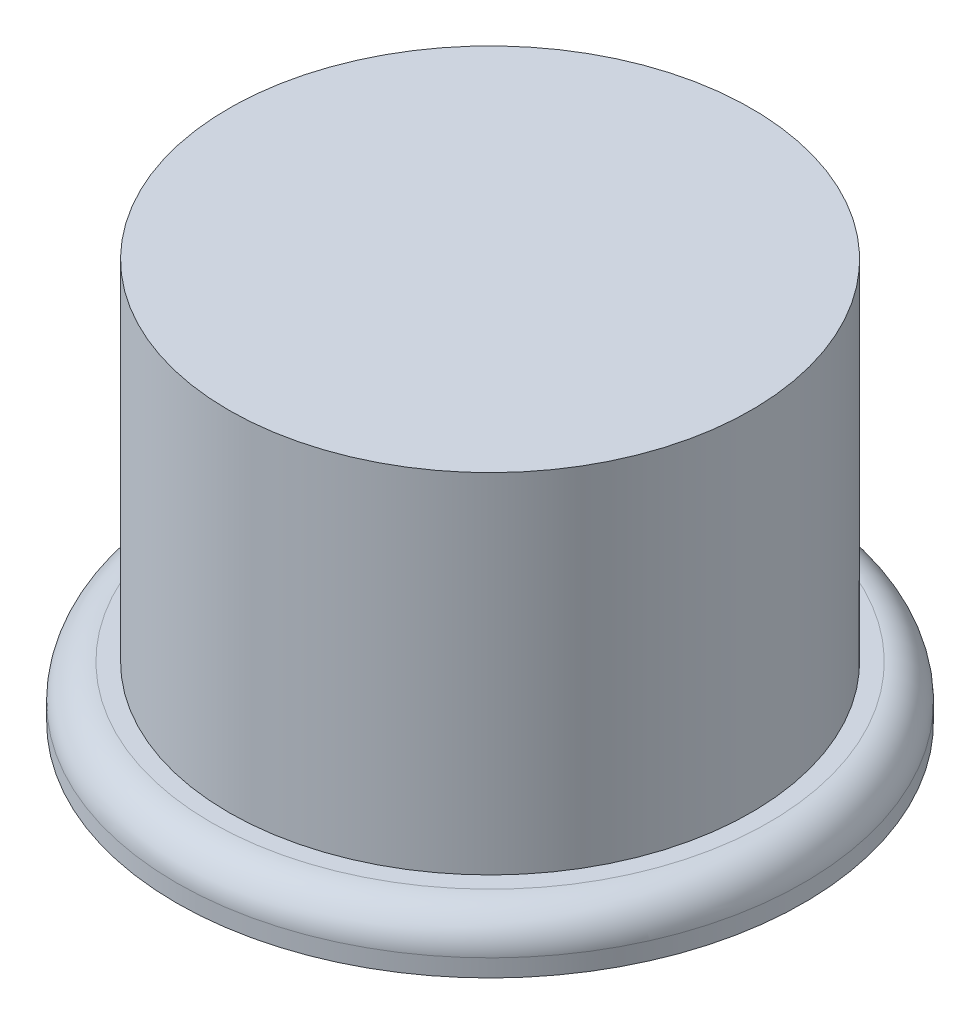
SolidWorks part; units mm, degrees
ref_plane "Plano frontal" through (0, 0, 0) normal (0, 0, 1) x (1, 0, 0)
ref_plane "Plano superior" through (0, 0, 0) normal (0, 1, 0) x (1, 0, 0)
ref_plane "Plano direito" through (0, 0, 0) normal (1, 0, 0) x (0, 0, -1)
sketch "Esboço1" plane through (0, 0, 0) normal (0, 1, 0) x (1, 0, 0)
  circle A0 centre (0, 0) radius 9
extrude "Ressalto-extrusão1" add sketch "Esboço1" along normal blind 1.5
fillet "Filete1" radius 1 1 edges at (0, 1.5, 9)
sketch "Esboço2" plane through (0, 1.5, 0) normal (0, 1, 0) x (1, 0, 0)
  circle A0 centre (0, 0) radius 7.5
  dimension "D1" = 15
extrude "Ressalto-extrusão2" add sketch "Esboço2" along normal blind 10
